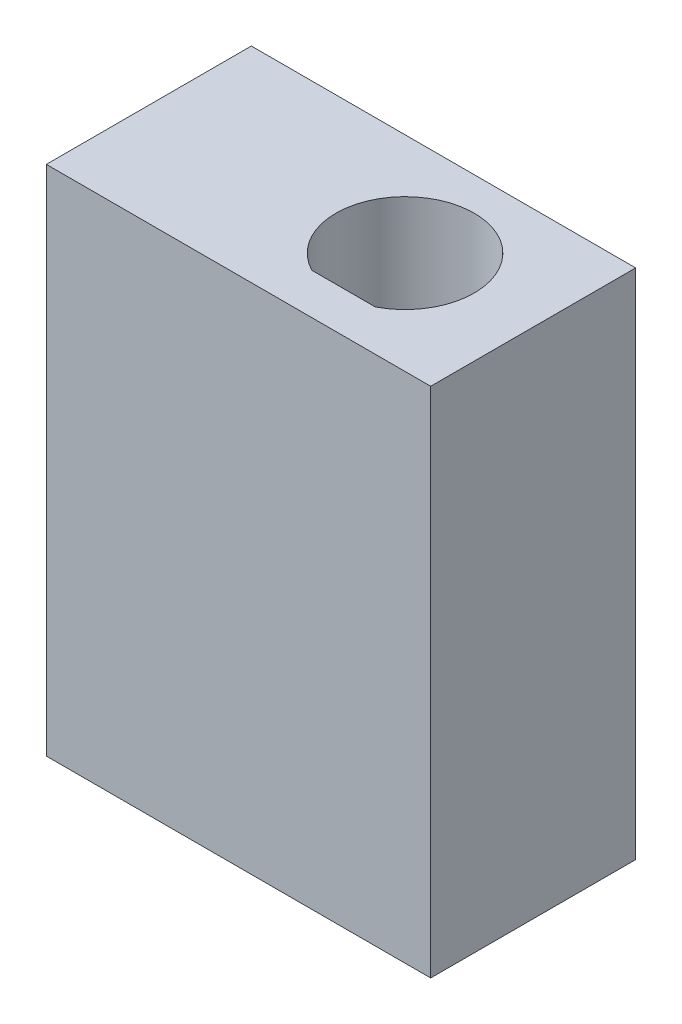
SolidWorks part; units mm, degrees
ref_plane "前视基准面" through (0, 0, 0) normal (0, 0, 1) x (1, 0, 0)
ref_plane "上视基准面" through (0, 0, 0) normal (0, 1, 0) x (1, 0, 0)
ref_plane "右视基准面" through (0, 0, 0) normal (1, 0, 0) x (0, 0, -1)
sketch "草图1" plane through (0, 0, 0) normal (0, 1, 0) x (1, 0, 0)
  line L0 (10, 8) -> (10, -0.6155) construction
  line L1 (0, 0) -> (15, 0)
  line L2 (0, 0) -> (0, 8)
  line L3 (0, 8) -> (15, 8)
  line L4 (15, 0) -> (15, 8)
  line L5 (8.7631, 1.6) -> (11.2369, 1.6)
  arc A0 (11.2369, 1.6) -> (8.7631, 1.6) centre (10, 4) ccw
  dimension "D3" = 5.4
  dimension "D4" = 4
  dimension "D1" = 15
  dimension "D2" = 8
  dimension "D5" = 2.4
  dimension "D6" = 10
extrude "凸台-拉伸1" add sketch "草图1" along normal blind 20
